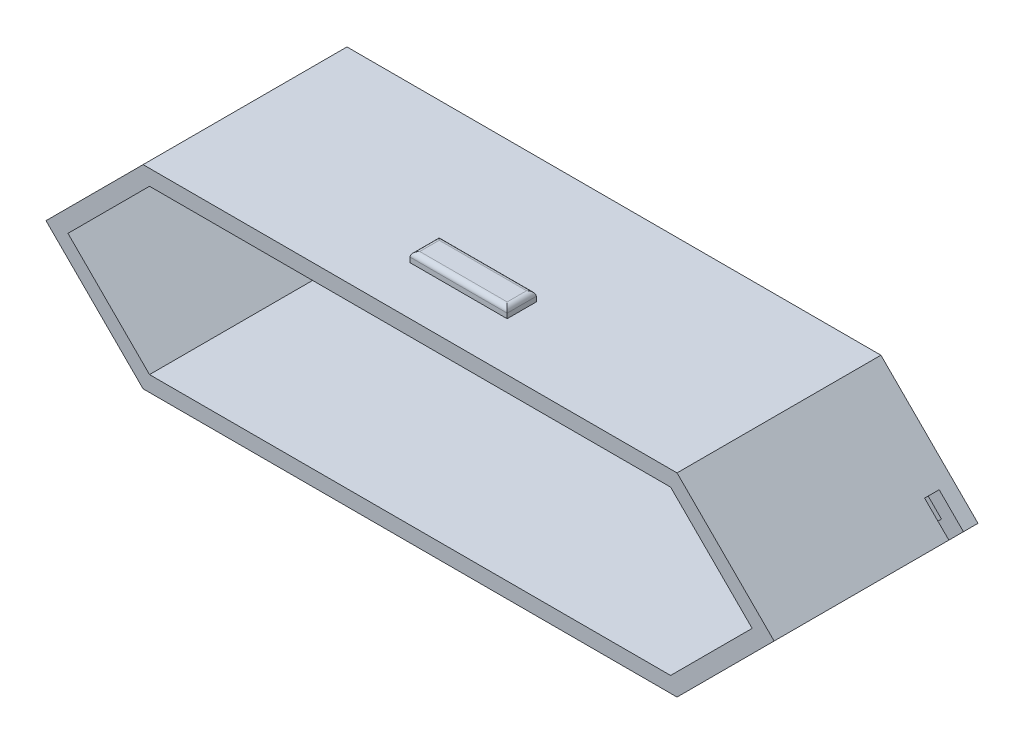
SolidWorks part; units mm, degrees
ref_plane "Plan de face" through (0, 0, 0) normal (0, 0, 1) x (1, 0, 0)
ref_plane "Plan de dessus" through (0, 0, 0) normal (0, 1, 0) x (1, 0, 0)
ref_plane "Plan de droite" through (0, 0, 0) normal (1, 0, 0) x (0, 0, -1)
sketch "Esquisse1" plane through (0, 0, 0) normal (0, 0, 1) x (1, 0, 0)
  line L5 (34.8454, 9.2514) -> (-20.1546, 9.2514)
  line L11 (-20.1546, 9.2514) -> (-30.1546, -0.7486)
  line L12 (-20.1546, 9.2514) -> (-20.1546, -0.7486) construction
  line L13 (-20.1546, -10.7486) -> (-30.1546, -0.7486)
  line L14 (7.3454, 9.2514) -> (7.3454, -0.7486) construction
  line L15 (-30.1546, -0.7486) -> (7.3454, -0.7486) construction
  line L16 (34.8454, -10.7486) -> (-20.1546, -10.7486)
  line L17 (34.8454, -10.7486) -> (44.8454, -0.7486)
  line L18 (34.8454, 9.2514) -> (44.8454, -0.7486)
  point P8 (7.3454, -10.7486)
  dimension "D1" = 37.5
  dimension "D2" = 27.5
  dimension "D3" = 10
extrude "Boss.-Extru.1" add sketch "Esquisse1" along normal blind 1
sketch "Esquisse2" plane through (0, 0, 1) normal (0, 0, 1) x (1, 0, 0)
  line L0 (-20.1546, -10.7486) -> (34.8454, -10.7486) construction
  line L1 (-30.1546, -0.7486) -> (-20.1546, -10.7486) construction
  line L2 (-20.1546, 9.2514) -> (-30.1546, -0.7486) construction
  line L3 (34.8454, -10.7486) -> (44.8454, -0.7486) construction
  line L4 (44.8454, -0.7486) -> (34.8454, 9.2514) construction
  line L5 (34.8454, 9.2514) -> (-20.1546, 9.2514) construction
  line L6 (-20.1546, -10.7486) -> (34.8454, -10.7486)
  line L7 (-30.1546, -0.7486) -> (-20.1546, -10.7486)
  line L8 (-20.1546, 9.2514) -> (-30.1546, -0.7486)
  line L9 (34.8454, -10.7486) -> (44.8454, -0.7486)
  line L10 (44.8454, -0.7486) -> (34.8454, 9.2514)
  line L11 (34.8454, 9.2514) -> (-20.1546, 9.2514)
  line L12 (-19.4919, 7.6514) -> (-27.8919, -0.7486)
  line L13 (-27.8919, -0.7486) -> (-19.4919, -9.1486)
  line L14 (-19.4919, -9.1486) -> (34.1826, -9.1486)
  line L15 (34.1826, -9.1486) -> (42.5826, -0.7486)
  line L16 (42.5826, -0.7486) -> (34.1826, 7.6514)
  line L17 (34.1826, 7.6514) -> (-19.4919, 7.6514)
  dimension "D1" = 1.6
extrude "Boss.-Extru.2" add sketch "Esquisse2" along normal blind 20
sketch "Esquisse5" plane through (0, 0, 0) normal (1, 0, 0) x (0, 0, -1)
  line L0 (-21, -0.7486) -> (0, -0.7486) construction
  line L1 (-3, -3.2486) -> (-1.5, -3.2486)
  line L2 (-3, -3.2486) -> (-3, 1.7514)
  line L3 (-3, 1.7514) -> (-1.5, 1.7514)
  line L4 (-1.5, -3.2486) -> (-1.5, 1.7514)
  line L5 (-3, -3.2486) -> (-1.5, 1.7514) construction
  line L6 (-3, 1.7514) -> (-1.5, -3.2486) construction
  line L7 (0, 9.2514) -> (0, -0.7486) construction
  point P0 (-2.25, -0.7486)
  dimension "D1" = 5
  dimension "D2" = 1.5
  dimension "D3" = 1.5
extrude "Enlèv. mat.-Extru.1" cut sketch "Esquisse5" against normal through all both and the other way through all
sketch "Esquisse9" plane through (0, 9.2514, 0) normal (0, 1, 0) x (1, 0, 0)
  line L0 (7.3454, -21) -> (7.3454, 0) construction
  line L1 (34.8454, -21) -> (-20.1546, -21) construction
  line L2 (34.8454, 0) -> (-20.1546, 0) construction
  line L4 (12.3454, -16) -> (2.3454, -16)
  line L5 (12.3454, -16) -> (12.3454, -13)
  line L6 (12.3454, -13) -> (2.3454, -13)
  line L7 (2.3454, -16) -> (2.3454, -13)
  line L8 (12.3454, -16) -> (2.3454, -13) construction
  line L9 (12.3454, -13) -> (2.3454, -16) construction
  point P6 (7.3454, -14.5)
  dimension "D1" = 10
  dimension "D2" = 3
  dimension "D3" = 5
extrude "Boss.-Extru.5" add sketch "Esquisse9" along normal blind 1
fillet "Congé1" radius 0.5 4 edges at (12.3454, 10.2514, 14.5) (7.3454, 10.2514, 13) (2.3454, 10.2514, 14.5) (7.3454, 10.2514, 16)
sketch "Esquisse10" plane through (0, -10.7486, 0) normal (0, -1, 0) x (1, 0, 0)
  line L0 (7.3454, 21) -> (7.3454, 0) construction
  line L1 (-20.1546, 21) -> (34.8454, 21) construction
  line L2 (-20.1546, 0) -> (34.8454, 0) construction
  line L4 (12.3454, 13) -> (2.3454, 13)
  line L5 (12.3454, 13) -> (12.3454, 16)
  line L6 (12.3454, 16) -> (2.3454, 16)
  line L7 (2.3454, 13) -> (2.3454, 16)
  line L8 (12.3454, 13) -> (2.3454, 16) construction
  line L9 (12.3454, 16) -> (2.3454, 13) construction
  point P6 (7.3454, 14.5)
  dimension "D1" = 10
  dimension "D2" = 3
  dimension "D3" = 5
extrude "Boss.-Extru.6" add sketch "Esquisse10" along normal blind 1
fillet "Congé2" radius 0.5 4 edges at (2.3454, -11.7486, 14.5) (7.3454, -11.7486, 13) (12.3454, -11.7486, 14.5) (7.3454, -11.7486, 16)
